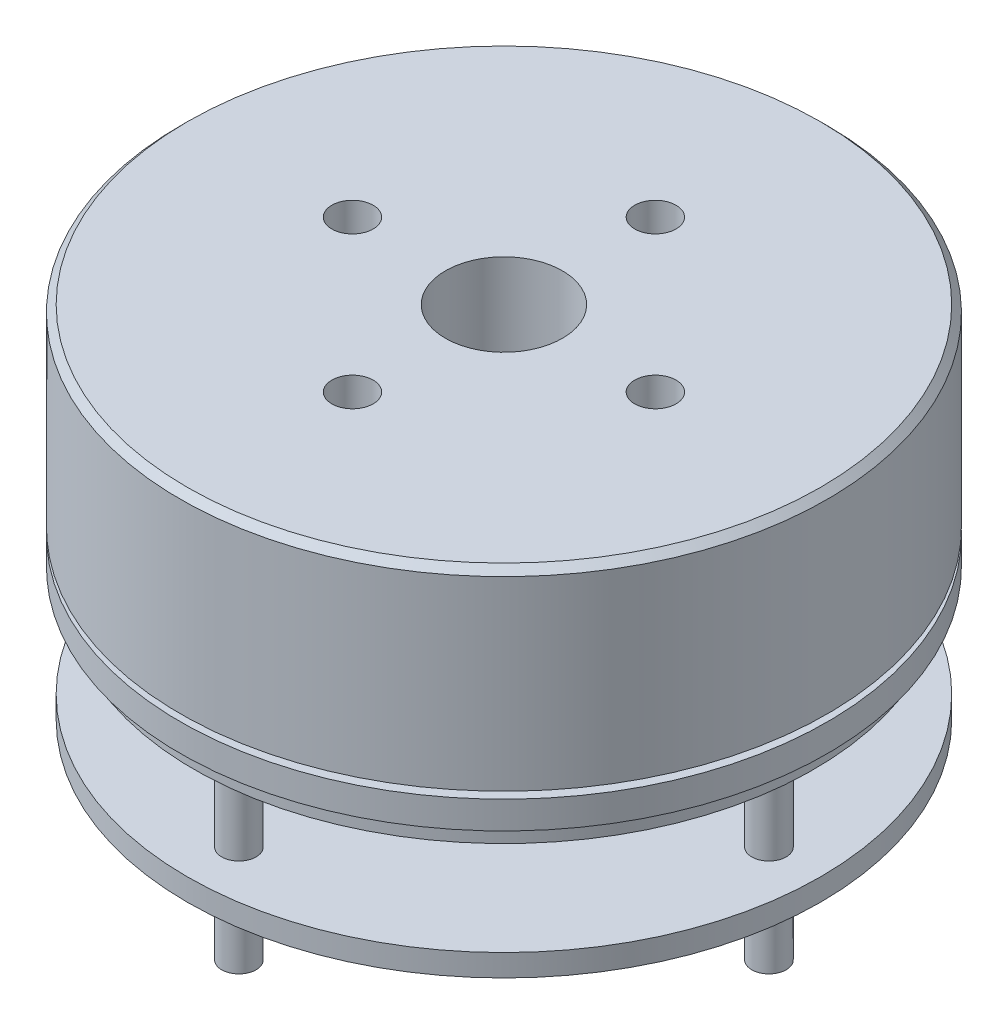
SolidWorks part; units mm, degrees
ref_plane "前视基准面" through (0, 0, 0) normal (0, 0, 1) x (1, 0, 0)
ref_plane "上视基准面" through (0, 0, 0) normal (0, 1, 0) x (1, 0, 0)
ref_plane "右视基准面" through (0, 0, 0) normal (1, 0, 0) x (0, 0, -1)
sketch "草图1" plane through (0, 0, 0) normal (0, 0, 1) x (1, 0, 0)
  line L1 (23, 22.1) -> (0, 22.1)
  line L4 (23.5, 21.6) -> (23.5, 8.1)
  line L6 (23.5, 8.1) -> (22.5, 8.1)
  line L7 (22.5, 8.1) -> (22.5, 7.6)
  line L8 (22.5, 7.6) -> (23.5, 7.6)
  line L9 (23.5, 7.6) -> (23.5, 5.6)
  line L10 (23.5, 21.6) -> (23, 22.1)
  line L12 (23.5, 5.6) -> (22.5, 5.6)
  line L13 (22.5, 5.6) -> (22.5, 4.1)
  line L14 (22.5, 4.1) -> (7.5, 4.1)
  line L17 (0, 0) -> (0, 22.1)
  line L18 (0, 0) -> (4.75, 0)
  line L20 (7.5, 4.1) -> (4.75, 0)
  point P3 (23.5, 22.1)
revolve "旋转1" add sketch "草图1" angle 360 about L17
sketch "草图2" plane through (0, 22.1, 0) normal (0, 1, 0) x (1, 0, 0)
  line L0 (0, 0) -> (0, 25.9186) construction
  circle A0 centre (0, 0) radius 11 construction
  circle A1 centre (0, 11) radius 1.5
  circle A2 centre (11, 0) radius 1.5
  circle A3 centre (0, -11) radius 1.5
  circle A4 centre (-11, 0) radius 1.5
  point P15 (0, 0)
  dimension "D1" = 4
extrude "切除-拉伸1" cut sketch "草图2" against normal blind 3
sketch "草图3" plane through (0, 22.1, 0) normal (0, 1, 0) x (1, 0, 0)
  circle A0 centre (0, 0) radius 4.25
extrude "切除-拉伸2" cut sketch "草图3" against normal blind 18
sketch "草图5" plane through (0, 4.1, 0) normal (0, -1, 0) x (1, 0, 0)
  line L0 (0, 0) -> (0, 24.6178) construction
  circle A0 centre (0, 0) radius 12.5 construction
  circle A2 centre (0, 12.5) radius 1
  circle A4 centre (12.5, 0) radius 1
  circle A5 centre (0, -12.5) radius 1
  circle A6 centre (-12.5, 0) radius 1
  point P17 (0, 0)
  dimension "D1" = 4
sketch "草图6" plane through (0, 4.1, 0) normal (0, -1, 0) x (1, 0, 0)
  circle A0 centre (0, 0) radius 19.25 construction
  circle A1 centre (0, 19.25) radius 1.25
  circle A2 centre (19.25, 0) radius 1.25
  circle A3 centre (0, -19.25) radius 1.25
  circle A4 centre (-19.25, 0) radius 1.25
  point P14 (0, 0)
  dimension "D1" = 4
extrude "凸台-拉伸1" add sketch "草图6" along normal blind 6.5
sketch "草图7" plane through (0, -2.4, 0) normal (0, -1, 0) x (1, 0, 0)
  circle A0 centre (0, 0) radius 23
extrude "凸台-拉伸2" add sketch "草图7" along normal blind 1.6
sketch "草图10" plane through (0, -4, 0) normal (0, -1, 0) x (1, 0, 0)
  circle A0 centre (0, 0) radius 19.25 construction
  circle A1 centre (0, 19.25) radius 1.25
  circle A2 centre (19.25, 0) radius 1.25
  circle A3 centre (0, -19.25) radius 1.25
  circle A4 centre (-19.25, 0) radius 1.25
  point P14 (0, 0)
  dimension "D1" = 4
extrude "凸台-拉伸3" add sketch "草图10" along normal blind 5.5
